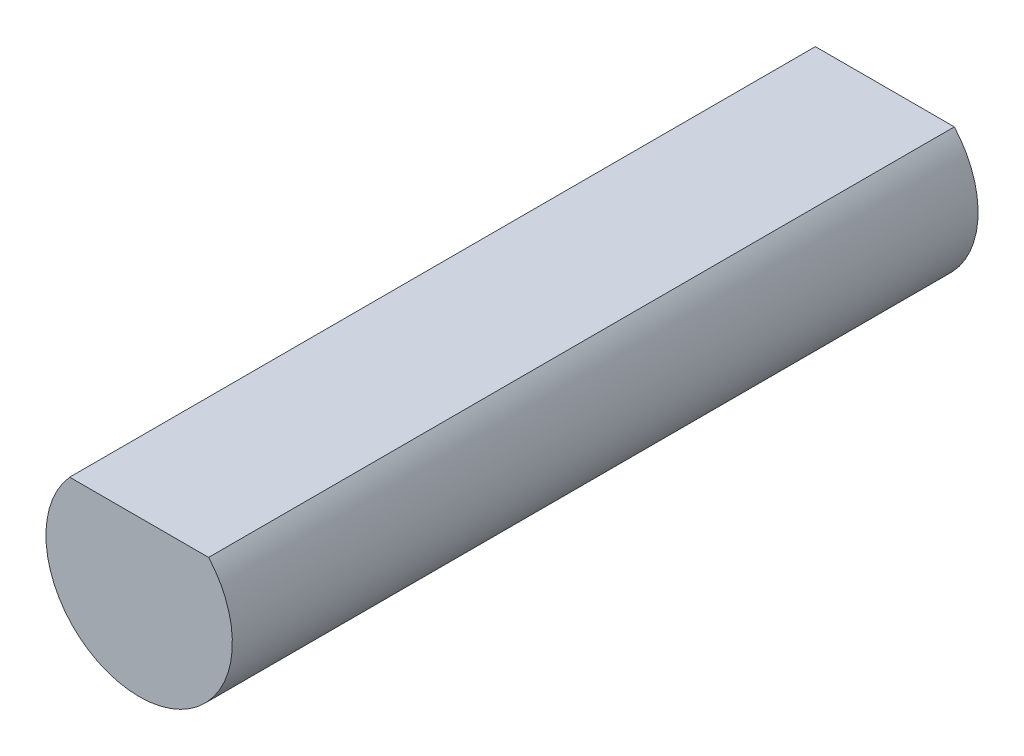
SolidWorks part; units mm, degrees
ref_plane "前视基准面" through (0, 0, 0) normal (0, 0, 1) x (1, 0, 0)
ref_plane "上视基准面" through (0, 0, 0) normal (0, 1, 0) x (1, 0, 0)
ref_plane "右视基准面" through (0, 0, 0) normal (1, 0, 0) x (0, 0, -1)
sketch "草图1" plane through (0, 0, 0) normal (0, 0, 1) x (1, 0, 0)
  line L0 (0, -1.5) -> (0, 1) construction
  line L1 (-1.118, 1) -> (1.118, 1)
  arc A0 (-1.118, 1) -> (1.118, 1) centre (0, 0) ccw
  dimension "D1" = 1.5
  dimension "D2" = 2.5
extrude "凸台-拉伸1" add sketch "草图1" along normal blind 12
